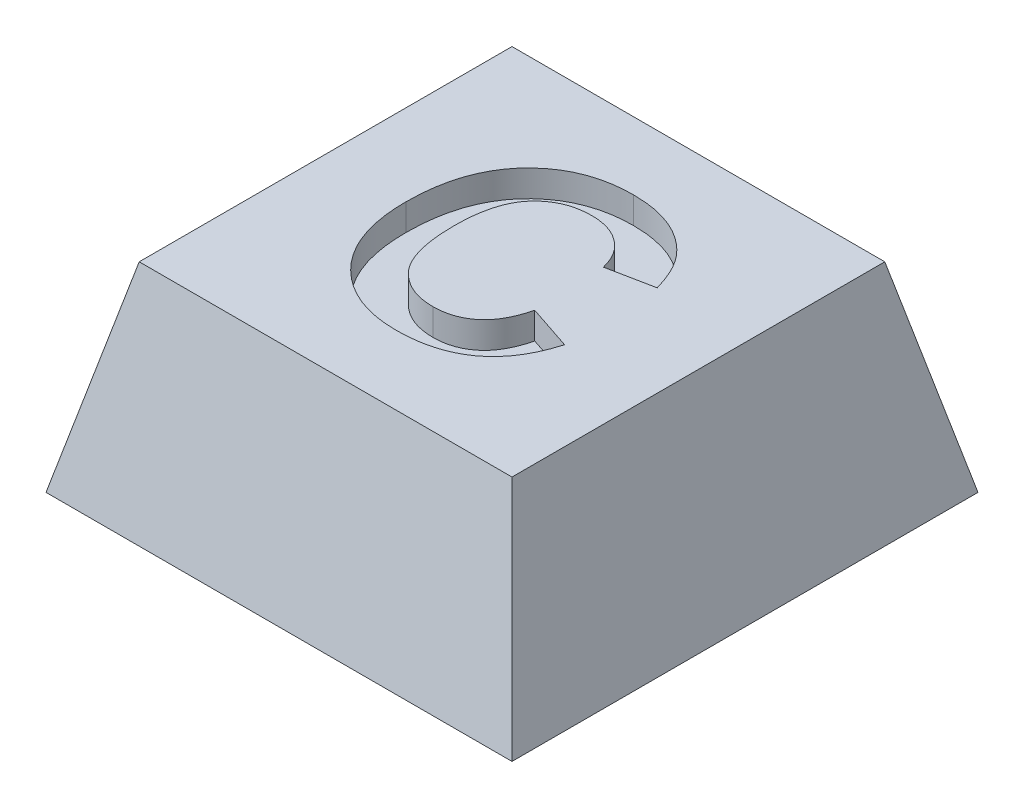
SolidWorks part; units mm, degrees
ref_plane "Front Plane" through (0, 0, 0) normal (0, 0, 1) x (1, 0, 0)
ref_plane "Top Plane" through (0, 0, 0) normal (0, 1, 0) x (1, 0, 0)
ref_plane "Right Plane" through (0, 0, 0) normal (1, 0, 0) x (0, 0, -1)
sketch "Sketch1" plane through (0, 0, 0) normal (0, 1, 0) x (1, 0, 0)
  line L1 (0, 0) -> (7, 0)
  line L2 (0, 0) -> (0, 7)
  line L3 (0, 7) -> (7, 7)
  line L4 (7, 0) -> (7, 7)
  dimension "D1" = 7
  dimension "D2" = 7
extrude "Boss-Extrude1" add sketch "Sketch1" along normal blind 3
sketch "Sketch2" plane through (0, 0, 0) normal (0, 0, 1) x (1, 0, 0)
  line L0 (0, 0) -> (0.7, 3)
  line L1 (0, 3) -> (7, 3) construction
  line L2 (0.7, 3) -> (0, 3)
  line L3 (0, 3) -> (0, 0)
  line L4 (7, 0) -> (6.3, 3)
  line L5 (6.3, 3) -> (7, 3)
  line L6 (7, 3) -> (7, 0)
  dimension "D1" = 0.7
  dimension "D2" = 0.7
extrude "Cut-Extrude1" cut sketch "Sketch2" against normal blind 7
sketch "Sketch3" plane through (0, 0, 0) normal (1, 0, 0) x (0, 0, -1)
  line L0 (0, 0) -> (0.7, 3)
  line L1 (7, 3) -> (0, 3) construction
  line L2 (0.7, 3) -> (0, 3)
  line L3 (0, 3) -> (0, 0)
  line L4 (7, 3) -> (6.3, 3)
  line L5 (6.3, 3) -> (7, 0)
  line L6 (7, 3) -> (7, 0)
  dimension "D1" = 0.7
  dimension "D2" = 0.7
extrude "Cut-Extrude2" cut sketch "Sketch3" along normal blind 11
sketch "Sketch4" plane through (0, 0, 0) normal (0, -1, 0) x (1, 0, 0)
  line L0 (3.5, 0) -> (3.5, -7) construction
  line L1 (0, 0) -> (7, 0) construction
  line L2 (7, -7) -> (0, -7) construction
  line L3 (0, -3.5) -> (7, -3.5) construction
  line L4 (0, -7) -> (0, 0) construction
  line L5 (7, 0) -> (7, -7) construction
  circle A0 centre (3.5, -3.5) radius 1.8
  dimension "D1" = 3.6
extrude "Cut-Extrude3" cut sketch "Sketch4" against normal blind 0.8
sketch "Sketch5" plane through (0, 3, 0) normal (0, 1, 0) x (1, 0, 0)
  text T0 "C" font "Arial" height 3.5
extrude "Cut-Extrude4" cut sketch "Sketch5" against normal blind 0.4
